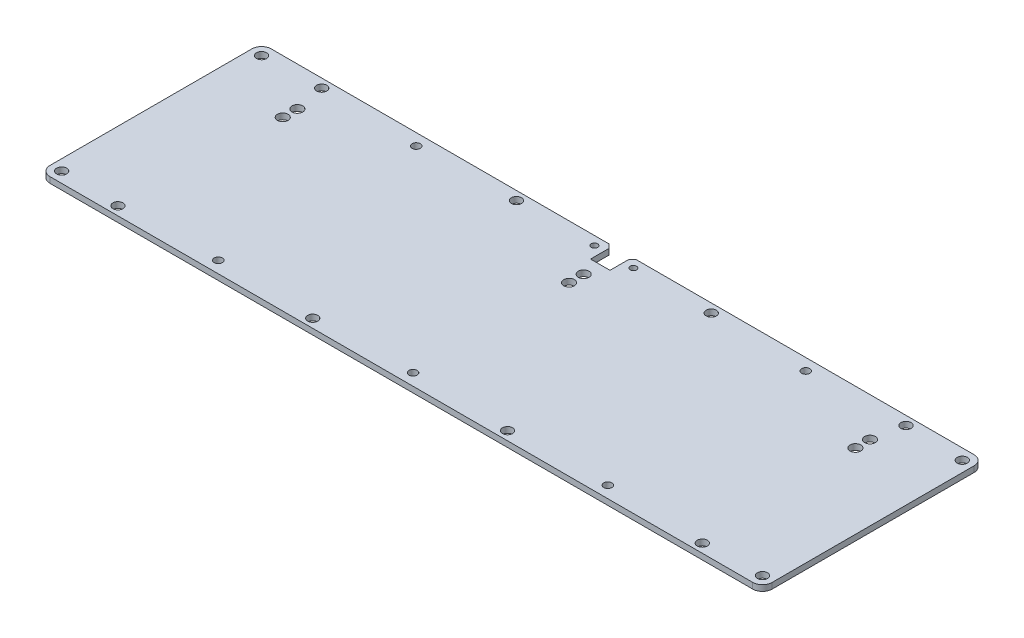
SolidWorks part; units mm, degrees
ref_plane "Front Plane" through (0, 0, 0) normal (0, 0, 1) x (1, 0, 0)
ref_plane "Top Plane" through (0, 0, 0) normal (0, 1, 0) x (1, 0, 0)
ref_plane "Right Plane" through (0, 0, 0) normal (1, 0, 0) x (0, 0, -1)
sketch "Sketch1" plane through (0, 0, 0) normal (0, 1, 0) x (1, 0, 0)
  line L0 (0, 108.6) -> (0, 5)
  line L1 (365.775, 0) -> (5, 0)
  line L2 (370.775, 108.6) -> (370.775, 5)
  line L3 (180.3875, 111.6) -> (178.3875, 113.6)
  line L4 (5, 113.6) -> (178.3875, 113.6)
  line L5 (180.3875, 111.6) -> (180.3875, 102.1)
  line L6 (180.3875, 102.1) -> (190.3875, 102.1)
  line L7 (190.3875, 111.6) -> (192.3875, 113.6)
  line L8 (190.3875, 111.6) -> (190.3875, 102.1)
  line L9 (192.3875, 113.6) -> (365.775, 113.6)
  arc A0 (365.775, 0) -> (370.775, 5) centre (365.775, 5) ccw
  arc A1 (370.775, 108.6) -> (365.775, 113.6) centre (365.775, 108.6) ccw
  arc A2 (0, 5) -> (5, 0) centre (5, 5) ccw
  circle A3 centre (5.5, 108.1) radius 2.6
  circle A4 centre (5.5, 5.5) radius 2.6
  circle A5 centre (365.275, 5.5) radius 2.6
  circle A6 centre (365.275, 108.1) radius 2.6
  arc A7 (5, 113.6) -> (0, 108.6) centre (5, 108.6) ccw
  circle A8 centre (35.3875, 4.5) radius 2.6
  circle A9 centre (135.3875, 4.5) radius 2.6
  circle A10 centre (335.3875, 4.5) radius 2.6
  circle A11 centre (235.3875, 4.5) radius 2.6
  circle A12 centre (35.3875, 109.1) radius 2.6
  circle A13 centre (135.3875, 109.1) radius 2.6
  circle A14 centre (335.3875, 109.1) radius 2.6
  circle A15 centre (235.3875, 109.1) radius 2.6
  circle A16 centre (195.3875, 109.1) radius 1.65
  circle A17 centre (175.3875, 109.1) radius 1.65
  circle A18 centre (38.3875, 86.1) radius 2.75
  circle A19 centre (38.3875, 93.6) radius 2.75
  circle A20 centre (332.3875, 86.1) radius 2.75
  circle A21 centre (332.3875, 93.6) radius 2.75
  circle A22 centre (185.3875, 86.1) radius 2.75
  circle A23 centre (185.3875, 93.6) radius 2.75
  circle A24 centre (85.3875, 107.6) radius 2.1
  circle A25 centre (285.3875, 107.6) radius 2.1
  circle A26 centre (85.3875, 6) radius 2.1
  circle A27 centre (185.3875, 6) radius 2.1
  circle A28 centre (285.3875, 6) radius 2.1
extrude "Boss-Extrude1" add sketch "Sketch1" against normal blind 3
